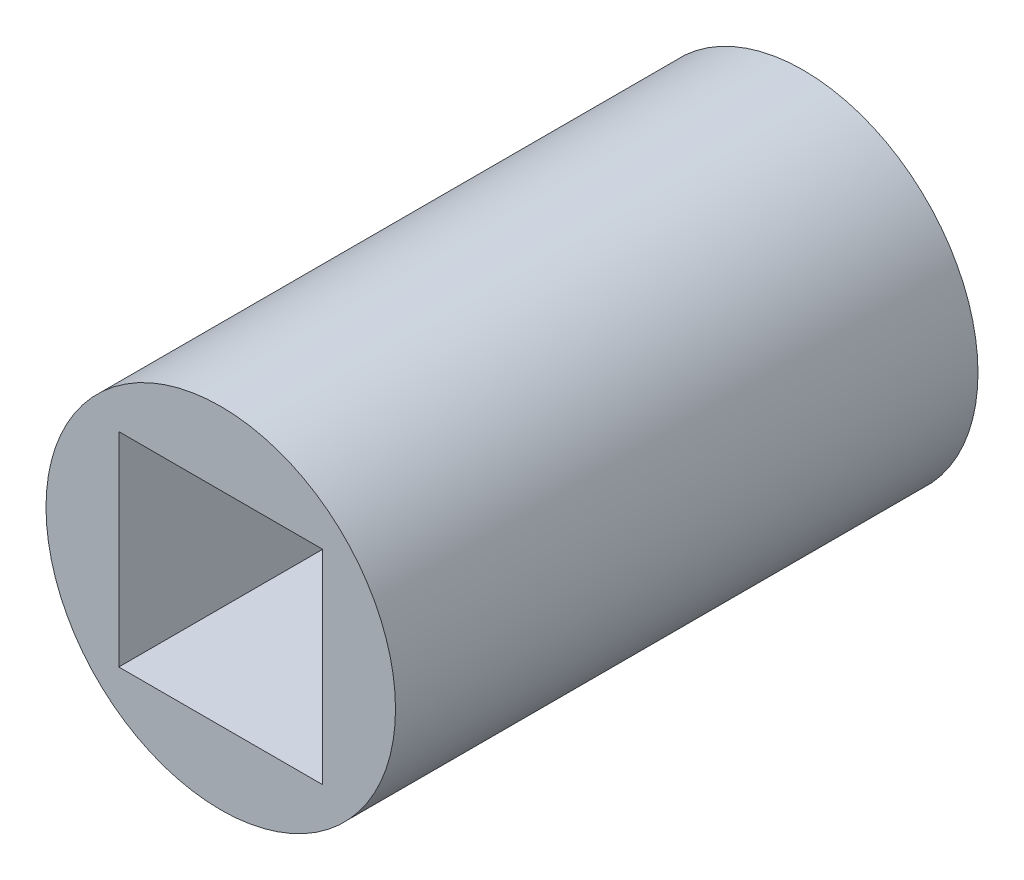
SolidWorks part; units mm, degrees
ref_plane "前视基准面" through (0, 0, 0) normal (0, 0, 1) x (1, 0, 0)
ref_plane "上视基准面" through (0, 0, 0) normal (0, 1, 0) x (1, 0, 0)
ref_plane "右视基准面" through (0, 0, 0) normal (1, 0, 0) x (0, 0, -1)
sketch "草图1" plane through (0, 0, 0) normal (0, 0, 1) x (1, 0, 0)
  line L0 (17.5, 35) -> (17.5, -49965) construction
  line L1 (0, 0) -> (35, 0)
  line L2 (0, 0) -> (0, 35)
  line L3 (0, 35) -> (35, 35)
  line L4 (35, 0) -> (35, 35)
  line L5 (0, 17.5) -> (50000, 17.5) construction
  circle A0 centre (17.5, 17.5) radius 30
  point P7 (17.5, 35)
  point P10 (0, 17.5)
  dimension "D3" = 60
  dimension "D1" = 35
  dimension "D2" = 35
extrude "凸台-拉伸1" add sketch "草图1" along normal blind 100
